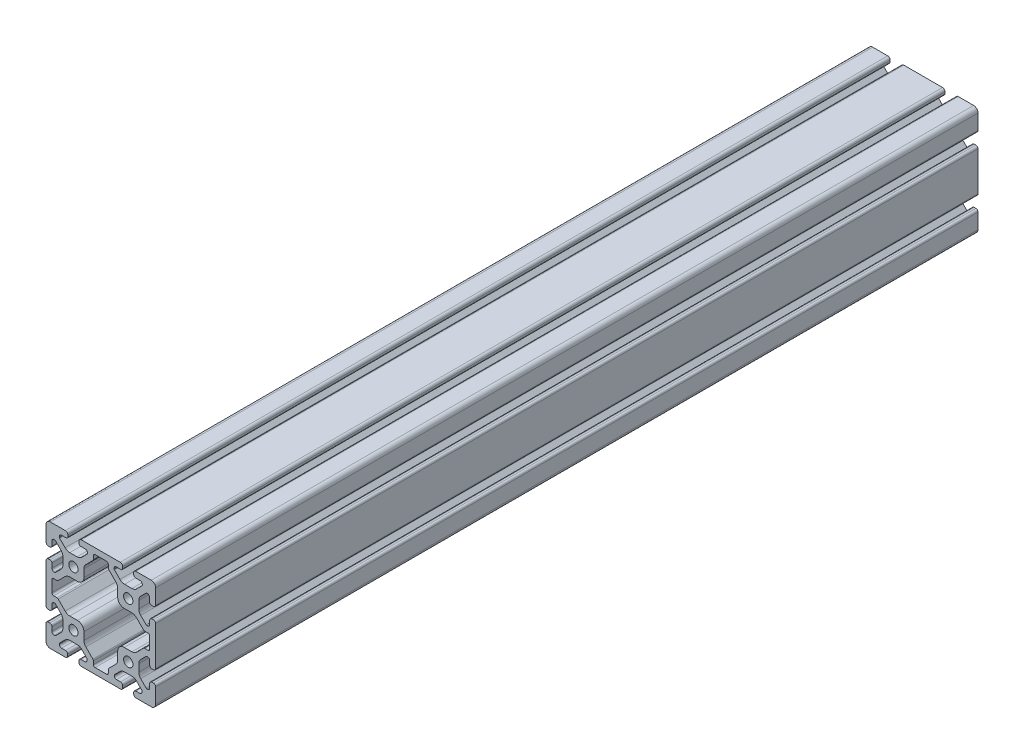
SolidWorks part; units mm, degrees
material "6061 Alloy"
ref_plane "Front Plane" through (0, 0, 0) normal (0, 0, 1) x (1, 0, 0)
ref_plane "Top Plane" through (0, 0, 0) normal (0, 1, 0) x (1, 0, 0)
ref_plane "Right Plane" through (0, 0, 0) normal (1, 0, 0) x (0, 0, -1)
sketch "Sketch1" plane through (0, 0, 0) normal (0, 0, 1) x (1, 0, 0)
  line L0 (0, -40) -> (0, 40) construction
  line L1 (0, 0) -> (-43.5804, 43.5804) construction
  line L2 (-20, 20) -> (-47.7323, 20) construction
  line L3 (-20, 20) -> (3.796, 43.796) construction
  line L4 (-20, 20) -> (-20, 43.5758) construction
  line L5 (-20, -27.7) -> (-20, -47.5576) construction
  line L131 (29.0912, 26.0365) -> (33.0827, 30.028)
  line L132 (27.7, 17.3222) -> (27.7, 22.6778)
  line L133 (29.0912, 13.9635) -> (33.0827, 9.972)
  line L134 (33.6201, 9.7494) -> (34.11, 9.7494)
  line L135 (35.68, 11.3194) -> (35.68, 14.2221)
  line L136 (37.25, 15.7921) -> (38.43, 15.7921)
  line L137 (40, 14.2221) -> (40, 7.0214)
  line L138 (40, 7.0214) -> (40, -7.0214)
  line L139 (40, -7.0214) -> (40, -14.2221)
  line L140 (38.43, -15.7921) -> (37.25, -15.7921)
  line L141 (35.68, -14.2221) -> (35.68, -11.3194)
  line L142 (33.6201, -9.7494) -> (34.11, -9.7494)
  line L143 (29.0912, -13.9635) -> (33.0827, -9.972)
  line L144 (27.7, -22.6778) -> (27.7, -17.3222)
  line L145 (29.0912, -26.0365) -> (33.0827, -30.028)
  line L146 (33.6201, -30.2506) -> (34.11, -30.2506)
  line L147 (35.68, -28.6806) -> (35.68, -25.7779)
  line L148 (37.25, -24.2079) -> (38.43, -24.2079)
  line L149 (40, -25.7779) -> (40, -33.0259)
  line L150 (40, -33.0259) -> (40, -36.83)
  line L151 (36.83, -40) -> (32.9998, -40)
  line L152 (32.9998, -40) -> (25.5696, -40)
  line L153 (23.9996, -38.43) -> (23.9996, -37.25)
  line L154 (25.5696, -35.68) -> (28.4723, -35.68)
  line L155 (30.0413, -34.0552) -> (30.0171, -33.3605)
  line L156 (29.7949, -32.8496) -> (26.0365, -29.0912)
  line L157 (17.3222, -27.7) -> (22.6778, -27.7)
  line L158 (10.035, -33.0197) -> (13.9635, -29.0912)
  line L159 (9.8124, -33.8926) -> (9.8124, -33.5571)
  line L160 (11.3824, -35.4626) -> (14.4246, -35.4626)
  line L161 (15.9946, -37.0326) -> (15.9946, -38.43)
  line L162 (14.4246, -40) -> (6.9987, -40)
  line L163 (6.9987, -40) -> (-6.9987, -40)
  line L164 (-6.9987, -40) -> (-14.4292, -40)
  line L165 (-15.9992, -38.43) -> (-15.9992, -37.25)
  line L166 (-14.4292, -35.68) -> (-11.5265, -35.68)
  line L167 (-9.9574, -34.0552) -> (-9.9816, -33.3618)
  line L168 (-10.2038, -32.8509) -> (-13.9635, -29.0912)
  line L169 (-22.6778, -27.7) -> (-17.3222, -27.7)
  line L170 (-30.028, -33.0827) -> (-26.0365, -29.0912)
  line L171 (-30.2506, -34.11) -> (-30.2506, -33.6201)
  line L172 (-28.6806, -35.68) -> (-25.7231, -35.68)
  line L173 (-24.1531, -37.25) -> (-24.1531, -38.43)
  line L174 (-25.7231, -40) -> (-33, -40)
  line L175 (-33, -40) -> (-36.83, -40)
  line L176 (-40, -36.83) -> (-40, -33.0191)
  line L177 (-40, -33.0191) -> (-40, -25.591)
  line L178 (-38.43, -24.021) -> (-37.25, -24.021)
  line L179 (-35.68, -28.4937) -> (-35.68, -25.591)
  line L180 (-34.0552, -30.0627) -> (-33.3827, -30.0392)
  line L181 (-32.8718, -29.8171) -> (-29.0912, -26.0365)
  line L182 (-27.7, -22.6778) -> (-27.7, -17.3222)
  line L183 (-29.0912, -13.9635) -> (-33.0827, -9.972)
  line L184 (-34.11, -9.7494) -> (-33.6201, -9.7494)
  line L185 (-35.68, -11.3194) -> (-35.68, -14.4473)
  line L186 (-38.43, -16.0173) -> (-37.25, -16.0173)
  line L187 (-40, -14.4473) -> (-40, -7.0169)
  line L188 (-40, -7.0169) -> (-40, 7.0169)
  line L189 (-40, 7.0169) -> (-40, 14.1348)
  line L190 (-38.1948, 15.94) -> (-36.9772, 15.94)
  line L191 (-35.68, 11.3194) -> (-35.68, 14.6428)
  line L192 (-34.11, 9.7494) -> (-33.6201, 9.7494)
  line L193 (-33.0827, 9.972) -> (-29.0912, 13.9635)
  line L194 (-27.7, 17.3222) -> (-27.7, 22.6778)
  line L195 (-29.0912, 26.0365) -> (-33.0827, 30.028)
  line L196 (-34.11, 30.2506) -> (-33.6201, 30.2506)
  line L197 (-35.68, 28.6806) -> (-35.68, 25.3572)
  line L198 (-38.1948, 24.06) -> (-36.9772, 24.06)
  line L199 (-40, 25.8652) -> (-40, 33.3181)
  line L200 (-40, 33.3181) -> (-40, 36.83)
  line L201 (-36.83, 40) -> (-33.0314, 40)
  line L202 (-33.0314, 40) -> (-25.8652, 40)
  line L203 (-24.06, 36.9772) -> (-24.06, 38.1948)
  line L204 (-25.3572, 35.68) -> (-28.7018, 35.68)
  line L205 (-30.285, 33.6069) -> (-30.285, 34.0968)
  line L206 (-30.0961, 33.1508) -> (-26.0365, 29.0912)
  line L207 (-22.6778, 27.7) -> (-17.3222, 27.7)
  line L208 (-13.9635, 29.0912) -> (-9.9039, 33.1508)
  line L209 (-9.715, 33.6069) -> (-9.715, 34.0968)
  line L210 (-14.6428, 35.68) -> (-11.2982, 35.68)
  line L211 (-15.94, 36.9772) -> (-15.94, 38.1948)
  line L212 (-14.1348, 40) -> (-6.9844, 40)
  line L213 (-6.9844, 40) -> (6.9844, 40)
  line L214 (6.9844, 40) -> (14.1348, 40)
  line L215 (15.94, 36.9772) -> (15.94, 38.1948)
  line L216 (14.6428, 35.68) -> (11.2982, 35.68)
  line L217 (9.715, 33.6069) -> (9.715, 34.0968)
  line L218 (9.9039, 33.1508) -> (13.9635, 29.0912)
  line L219 (17.3222, 27.7) -> (22.6778, 27.7)
  line L220 (26.0365, 29.0912) -> (30.028, 33.0827)
  line L221 (30.2506, 33.6201) -> (30.2506, 34.11)
  line L222 (25.5409, 35.679) -> (28.6258, 35.679)
  line L223 (23.9709, 37.249) -> (23.9709, 38.43)
  line L224 (25.5409, 40) -> (36.83, 40)
  line L226 (40, 36.83) -> (40, 32.9339)
  line L227 (40, 32.9339) -> (40, 25.7779)
  line L228 (38.43, 24.2079) -> (37.0956, 24.2079)
  line L229 (35.5256, 25.7779) -> (35.5256, 28.6806)
  line L230 (33.6201, 30.2506) -> (33.9556, 30.2506)
  line L231 (17.07, 12.32) -> (22.6578, 12.32)
  line L232 (26.0165, 10.9288) -> (31.1439, 5.8014)
  line L233 (32.0419, 5.4294) -> (34.41, 5.4294)
  line L234 (35.68, -4.1594) -> (35.68, 4.1594)
  line L235 (32.0419, -5.4294) -> (34.41, -5.4294)
  line L236 (26.0165, -10.9288) -> (31.1439, -5.8014)
  line L237 (17.07, -12.32) -> (22.6578, -12.32)
  line L238 (12.32, -22.6578) -> (12.32, -17.07)
  line L239 (5.8014, -31.1439) -> (10.9288, -26.0165)
  line L240 (5.4294, -34.41) -> (5.4294, -32.0419)
  line L241 (-4.1594, -35.68) -> (4.1594, -35.68)
  line L242 (-5.4294, -34.41) -> (-5.4294, -32.0419)
  line L243 (-5.8014, -31.1439) -> (-10.9288, -26.0165)
  line L244 (-12.32, -22.6578) -> (-12.32, -17.07)
  line L245 (-22.6578, -12.32) -> (-17.07, -12.32)
  line L246 (-26.0165, -10.9288) -> (-31.1439, -5.8014)
  line L247 (-34.41, -5.4294) -> (-32.0419, -5.4294)
  line L248 (-35.68, -4.1594) -> (-35.68, 4.1594)
  line L249 (-34.41, 5.4294) -> (-32.0419, 5.4294)
  line L250 (-31.1439, 5.8014) -> (-26.0165, 10.9288)
  line L251 (-22.6578, 12.32) -> (-17.07, 12.32)
  line L252 (-12.32, 17.07) -> (-12.32, 22.6578)
  line L253 (-10.9288, 26.0165) -> (-5.8014, 31.1439)
  line L254 (-5.4294, 32.0419) -> (-5.4294, 34.41)
  line L255 (-4.1594, 35.68) -> (4.1594, 35.68)
  line L256 (5.4294, 32.0419) -> (5.4294, 34.41)
  line L257 (5.8014, 31.1439) -> (10.9288, 26.0165)
  line L258 (12.32, 17.07) -> (12.32, 22.6578)
  line L260 (-40, 0) -> (40, 0) construction
  circle A116 centre (-20, 20) radius 3.4
  circle A117 centre (20, 20) radius 3.4
  circle A118 centre (20, -20) radius 3.4
  circle A119 centre (-20, -20) radius 3.4
  arc A120 (29.0912, 26.0365) -> (27.7, 22.6778) centre (32.45, 22.6778) ccw
  arc A121 (27.7, 17.3222) -> (29.0912, 13.9635) centre (32.45, 17.3222) ccw
  arc A122 (33.0827, 9.972) -> (33.6201, 9.7494) centre (33.6201, 10.5094) ccw
  arc A123 (34.11, 9.7494) -> (35.68, 11.3194) centre (34.11, 11.3194) ccw
  arc A124 (37.25, 15.7921) -> (35.68, 14.2221) centre (37.25, 14.2221) ccw
  arc A125 (40, 14.2221) -> (38.43, 15.7921) centre (38.43, 14.2221) ccw
  arc A126 (38.43, -15.7921) -> (40, -14.2221) centre (38.43, -14.2221) ccw
  arc A127 (35.68, -14.2221) -> (37.25, -15.7921) centre (37.25, -14.2221) ccw
  arc A128 (35.68, -11.3194) -> (34.11, -9.7494) centre (34.11, -11.3194) ccw
  arc A129 (33.6201, -9.7494) -> (33.0827, -9.972) centre (33.6201, -10.5094) ccw
  arc A130 (29.0912, -13.9635) -> (27.7, -17.3222) centre (32.45, -17.3222) ccw
  arc A131 (27.7, -22.6778) -> (29.0912, -26.0365) centre (32.45, -22.6778) ccw
  arc A132 (33.0827, -30.028) -> (33.6201, -30.2506) centre (33.6201, -29.4906) ccw
  arc A133 (34.11, -30.2506) -> (35.68, -28.6806) centre (34.11, -28.6806) ccw
  arc A134 (37.25, -24.2079) -> (35.68, -25.7779) centre (37.25, -25.7779) ccw
  arc A135 (40, -25.7779) -> (38.43, -24.2079) centre (38.43, -25.7779) ccw
  arc A136 (36.83, -40) -> (40, -36.83) centre (36.83, -36.83) ccw
  arc A137 (23.9996, -38.43) -> (25.5696, -40) centre (25.5696, -38.43) ccw
  arc A138 (25.5696, -35.68) -> (23.9996, -37.25) centre (25.5696, -37.25) ccw
  arc A139 (28.4723, -35.68) -> (30.0413, -34.0552) centre (28.4723, -34.11) ccw
  arc A140 (30.0171, -33.3605) -> (29.7949, -32.8496) centre (29.2575, -33.387) ccw
  arc A141 (26.0365, -29.0912) -> (22.6778, -27.7) centre (22.6778, -32.45) ccw
  arc A142 (17.3222, -27.7) -> (13.9635, -29.0912) centre (17.3222, -32.45) ccw
  arc A143 (10.035, -33.0197) -> (9.8124, -33.5571) centre (10.5724, -33.5571) ccw
  arc A144 (9.8124, -33.8926) -> (11.3824, -35.4626) centre (11.3824, -33.8926) ccw
  arc A145 (15.9946, -37.0326) -> (14.4246, -35.4626) centre (14.4246, -37.0326) ccw
  arc A146 (14.4246, -40) -> (15.9946, -38.43) centre (14.4246, -38.43) ccw
  arc A147 (-15.9992, -38.43) -> (-14.4292, -40) centre (-14.4292, -38.43) ccw
  arc A148 (-14.4292, -35.68) -> (-15.9992, -37.25) centre (-14.4292, -37.25) ccw
  arc A149 (-11.5265, -35.68) -> (-9.9574, -34.0552) centre (-11.5265, -34.11) ccw
  arc A150 (-9.9816, -33.3618) -> (-10.2038, -32.8509) centre (-10.7412, -33.3883) ccw
  arc A151 (-13.9635, -29.0912) -> (-17.3222, -27.7) centre (-17.3222, -32.45) ccw
  arc A152 (-22.6778, -27.7) -> (-26.0365, -29.0912) centre (-22.6778, -32.45) ccw
  arc A153 (-30.028, -33.0827) -> (-30.2506, -33.6201) centre (-29.4906, -33.6201) ccw
  arc A154 (-30.2506, -34.11) -> (-28.6806, -35.68) centre (-28.6806, -34.11) ccw
  arc A155 (-24.1531, -37.25) -> (-25.7231, -35.68) centre (-25.7231, -37.25) ccw
  arc A156 (-25.7231, -40) -> (-24.1531, -38.43) centre (-25.7231, -38.43) ccw
  arc A157 (-40, -36.83) -> (-36.83, -40) centre (-36.83, -36.83) ccw
  arc A158 (-38.43, -24.021) -> (-40, -25.591) centre (-38.43, -25.591) ccw
  arc A159 (-35.68, -25.591) -> (-37.25, -24.021) centre (-37.25, -25.591) ccw
  arc A160 (-35.68, -28.4937) -> (-34.0552, -30.0627) centre (-34.11, -28.4937) ccw
  arc A161 (-33.3827, -30.0392) -> (-32.8718, -29.8171) centre (-33.4092, -29.2797) ccw
  arc A162 (-29.0912, -26.0365) -> (-27.7, -22.6778) centre (-32.45, -22.6778) ccw
  arc A163 (-27.7, -17.3222) -> (-29.0912, -13.9635) centre (-32.45, -17.3222) ccw
  arc A164 (-33.0827, -9.972) -> (-33.6201, -9.7494) centre (-33.6201, -10.5094) ccw
  arc A165 (-34.11, -9.7494) -> (-35.68, -11.3194) centre (-34.11, -11.3194) ccw
  arc A166 (-37.25, -16.0173) -> (-35.68, -14.4473) centre (-37.25, -14.4473) ccw
  arc A167 (-40, -14.4473) -> (-38.43, -16.0173) centre (-38.43, -14.4473) ccw
  arc A168 (-38.1948, 15.94) -> (-40, 14.1348) centre (-38.1948, 14.1348) ccw
  arc A169 (-35.68, 14.6428) -> (-36.9772, 15.94) centre (-36.9772, 14.6428) ccw
  arc A170 (-35.68, 11.3194) -> (-34.11, 9.7494) centre (-34.11, 11.3194) ccw
  arc A171 (-33.6201, 9.7494) -> (-33.0827, 9.972) centre (-33.6201, 10.5094) ccw
  arc A172 (-29.0912, 13.9635) -> (-27.7, 17.3222) centre (-32.45, 17.3222) ccw
  arc A173 (-27.7, 22.6778) -> (-29.0912, 26.0365) centre (-32.45, 22.6778) ccw
  arc A174 (-33.0827, 30.028) -> (-33.6201, 30.2506) centre (-33.6201, 29.4906) ccw
  arc A175 (-34.11, 30.2506) -> (-35.68, 28.6806) centre (-34.11, 28.6806) ccw
  arc A176 (-36.9772, 24.06) -> (-35.68, 25.3572) centre (-36.9772, 25.3572) ccw
  arc A177 (-40, 25.8652) -> (-38.1948, 24.06) centre (-38.1948, 25.8652) ccw
  arc A178 (-36.83, 40) -> (-40, 36.83) centre (-36.83, 36.83) ccw
  arc A179 (-24.06, 38.1948) -> (-25.8652, 40) centre (-25.8652, 38.1948) ccw
  arc A180 (-25.3572, 35.68) -> (-24.06, 36.9772) centre (-25.3572, 36.9772) ccw
  arc A181 (-28.7018, 35.68) -> (-30.285, 34.0968) centre (-28.7018, 34.0968) ccw
  arc A182 (-30.285, 33.6069) -> (-30.0961, 33.1508) centre (-29.6399, 33.6069) ccw
  arc A183 (-26.0365, 29.0912) -> (-22.6778, 27.7) centre (-22.6778, 32.45) ccw
  arc A184 (-17.3222, 27.7) -> (-13.9635, 29.0912) centre (-17.3222, 32.45) ccw
  arc A185 (-9.9039, 33.1508) -> (-9.715, 33.6069) centre (-10.3601, 33.6069) ccw
  arc A186 (-9.715, 34.0968) -> (-11.2982, 35.68) centre (-11.2982, 34.0968) ccw
  arc A187 (-15.94, 36.9772) -> (-14.6428, 35.68) centre (-14.6428, 36.9772) ccw
  arc A188 (-14.1348, 40) -> (-15.94, 38.1948) centre (-14.1348, 38.1948) ccw
  arc A189 (15.94, 38.1948) -> (14.1348, 40) centre (14.1348, 38.1948) ccw
  arc A190 (14.6428, 35.68) -> (15.94, 36.9772) centre (14.6428, 36.9772) ccw
  arc A191 (11.2982, 35.68) -> (9.715, 34.0968) centre (11.2982, 34.0968) ccw
  arc A192 (9.715, 33.6069) -> (9.9039, 33.1508) centre (10.3601, 33.6069) ccw
  arc A193 (13.9635, 29.0912) -> (17.3222, 27.7) centre (17.3222, 32.45) ccw
  arc A194 (22.6778, 27.7) -> (26.0365, 29.0912) centre (22.6778, 32.45) ccw
  arc A195 (30.028, 33.0827) -> (30.2506, 33.6201) centre (29.4906, 33.6201) ccw
  arc A196 (30.2506, 34.11) -> (28.6258, 35.679) centre (28.6806, 34.11) ccw
  arc A197 (23.9709, 37.249) -> (25.5409, 35.679) centre (25.5409, 37.249) ccw
  arc A198 (25.5409, 40) -> (23.9709, 38.43) centre (25.5409, 38.43) ccw
  arc A199 (40, 36.83) -> (36.83, 40) centre (36.83, 36.83) ccw
  arc A200 (38.43, 24.2079) -> (40, 25.7779) centre (38.43, 25.7779) ccw
  arc A201 (35.5256, 25.7779) -> (37.0956, 24.2079) centre (37.0956, 25.7779) ccw
  arc A202 (35.5256, 28.6806) -> (33.9556, 30.2506) centre (33.9556, 28.6806) ccw
  arc A203 (33.6201, 30.2506) -> (33.0827, 30.028) centre (33.6201, 29.4906) ccw
  arc A204 (26.0165, 10.9288) -> (22.6578, 12.32) centre (22.6578, 7.57) ccw
  arc A205 (31.1439, 5.8014) -> (32.0419, 5.4294) centre (32.0419, 6.6994) ccw
  arc A206 (35.68, 4.1594) -> (34.41, 5.4294) centre (34.41, 4.1594) ccw
  arc A207 (34.41, -5.4294) -> (35.68, -4.1594) centre (34.41, -4.1594) ccw
  arc A208 (32.0419, -5.4294) -> (31.1439, -5.8014) centre (32.0419, -6.6994) ccw
  arc A209 (22.6578, -12.32) -> (26.0165, -10.9288) centre (22.6578, -7.57) ccw
  arc A210 (17.07, -12.32) -> (12.32, -17.07) centre (17.07, -17.07) ccw
  arc A211 (10.9288, -26.0165) -> (12.32, -22.6578) centre (7.57, -22.6578) ccw
  arc A212 (5.8014, -31.1439) -> (5.4294, -32.0419) centre (6.6994, -32.0419) ccw
  arc A213 (4.1594, -35.68) -> (5.4294, -34.41) centre (4.1594, -34.41) ccw
  arc A214 (-5.4294, -34.41) -> (-4.1594, -35.68) centre (-4.1594, -34.41) ccw
  arc A215 (-5.4294, -32.0419) -> (-5.8014, -31.1439) centre (-6.6994, -32.0419) ccw
  arc A216 (-12.32, -22.6578) -> (-10.9288, -26.0165) centre (-7.57, -22.6578) ccw
  arc A217 (-12.32, -17.07) -> (-17.07, -12.32) centre (-17.07, -17.07) ccw
  arc A218 (-26.0165, -10.9288) -> (-22.6578, -12.32) centre (-22.6578, -7.57) ccw
  arc A219 (-31.1439, -5.8014) -> (-32.0419, -5.4294) centre (-32.0419, -6.6994) ccw
  arc A220 (-35.68, -4.1594) -> (-34.41, -5.4294) centre (-34.41, -4.1594) ccw
  arc A221 (-34.41, 5.4294) -> (-35.68, 4.1594) centre (-34.41, 4.1594) ccw
  arc A222 (-32.0419, 5.4294) -> (-31.1439, 5.8014) centre (-32.0419, 6.6994) ccw
  arc A223 (-22.6578, 12.32) -> (-26.0165, 10.9288) centre (-22.6578, 7.57) ccw
  arc A224 (-17.07, 12.32) -> (-12.32, 17.07) centre (-17.07, 17.07) ccw
  arc A225 (-10.9288, 26.0165) -> (-12.32, 22.6578) centre (-7.57, 22.6578) ccw
  arc A226 (-5.8014, 31.1439) -> (-5.4294, 32.0419) centre (-6.6994, 32.0419) ccw
  arc A227 (-4.1594, 35.68) -> (-5.4294, 34.41) centre (-4.1594, 34.41) ccw
  arc A228 (5.4294, 34.41) -> (4.1594, 35.68) centre (4.1594, 34.41) ccw
  arc A229 (5.4294, 32.0419) -> (5.8014, 31.1439) centre (6.6994, 32.0419) ccw
  arc A230 (12.32, 22.6578) -> (10.9288, 26.0165) centre (7.57, 22.6578) ccw
  arc A231 (12.32, 17.07) -> (17.07, 12.32) centre (17.07, 17.07) ccw
  dimension "D8" = 6.8
  dimension "D1" = 80
  dimension "D2" = 40
  dimension "D3" = 20
  dimension "D4" = 20.57
  dimension "D5" = 4.32
  dimension "D6" = 4.32
  dimension "D7" = 8.12
  dimension "D9" = 4.32
  dimension "D10" = 12.3
extrude "Extrude1" add sketch "Sketch1" against normal blind 600
hole_wizard "M8x1.25 Tapped Hole4" positions "Sketch3" profile "Sketch2" tap size "M8x1.25" standard "ANSI Metric"
sketch "Sketch3" plane through (0, 0, 0) normal (0, 0, 1) x (1, 0, 0)
  point P0 (-20, 20)
  point P3 (20, 20)
  point P6 (20, -20)
  point P9 (-20, -20)
sketch "Sketch2" plane through (-20, 20, 0) normal (1, 0, 0) x (0, -1, 0)
  line L0 (0, 0) -> (0, 11.7929)
  line L1 (0, 11.7929) -> (3.4, 9.75)
  line L2 (3.4, 9.75) -> (3.4, 0)
  line L5 (3.4, 0) -> (0, 0)
  line L10 (0, 11.7929) -> (-3.4, 9.75) construction
  line L11 (0, -6.35) -> (0, 107.95) construction
  dimension "Tap Drill Dia." = 6.8
  dimension "Tap Drill Depth" = 9.75
  dimension "Drill Angle" = 118
hole_wizard "M8x1.25 Tapped Hole3" positions "Sketch7" profile "Sketch6" tap size "M8x1.25" standard "ANSI Metric"
sketch "Sketch7" plane through (0, 0, -600) normal (0, 0, -1) x (-1, 0, 0)
  point P0 (-20, 20)
  point P3 (20, 20)
  point P6 (20, -20)
  point P9 (-20, -20)
sketch "Sketch6" plane through (20, 20, -600) normal (1, 0, 0) x (0, 1, 0)
  line L0 (0, 0) -> (0, 33.6929)
  line L1 (0, 33.6929) -> (3.4, 31.65)
  line L2 (3.4, 31.65) -> (3.4, 0)
  line L5 (3.4, 0) -> (0, 0)
  line L10 (0, 33.6929) -> (-3.4, 31.65) construction
  line L11 (0, -6.35) -> (0, 107.95) construction
  dimension "Tap Drill Dia." = 6.8
  dimension "Tap Drill Depth" = 31.65
  dimension "Drill Angle" = 118
